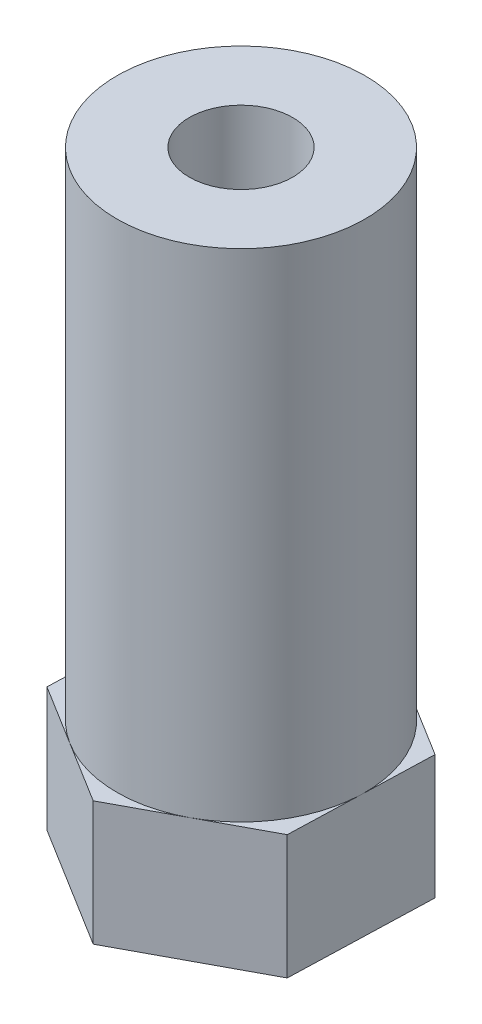
SolidWorks part; units mm, degrees
ref_plane "前视基准面" through (0, 0, 0) normal (0, 0, 1) x (1, 0, 0)
ref_plane "上视基准面" through (0, 0, 0) normal (0, 1, 0) x (1, 0, 0)
ref_plane "右视基准面" through (0, 0, 0) normal (1, 0, 0) x (0, 0, -1)
other "Configuration Table"
sketch "草图1" plane through (0, 0, 0) normal (0, 1, 0) x (1, 0, 0)
  line L1 (5.8875, -3.6521) -> (6.1065, 3.2727)
  line L2 (6.1065, 3.2727) -> (0.2191, 6.9247)
  line L3 (0.2191, 6.9247) -> (-5.8875, 3.6521)
  line L4 (-5.8875, 3.6521) -> (-6.1065, -3.2727)
  line L5 (-6.1065, -3.2727) -> (-0.2191, -6.9247)
  line L6 (-0.2191, -6.9247) -> (5.8875, -3.6521)
  circle A0 centre (0, 0) radius 6 construction
  dimension "D1" = 12
extrude "凸台-拉伸1" add sketch "草图1" along normal blind 6
sketch "草图2" plane through (0, 6, 0) normal (0, 1, 0) x (1, 0, 0)
  circle A0 centre (0, 0) radius 6
extrude "凸台-拉伸2" add sketch "草图2" along normal blind 24
sketch "草图3" plane through (0, 30, 0) normal (0, 1, 0) x (1, 0, 0)
  circle A0 centre (0, 0) radius 2.5
  dimension "D1" = 5
extrude "切除-拉伸1" cut sketch "草图3" against normal blind 24
sketch "草图4" plane through (0, 0, 0) normal (0, -1, 0) x (1, 0, 0)
  circle A0 centre (0, 0) radius 2
  dimension "D1" = 4
extrude "切除-拉伸2" cut sketch "草图4" against normal blind 6
